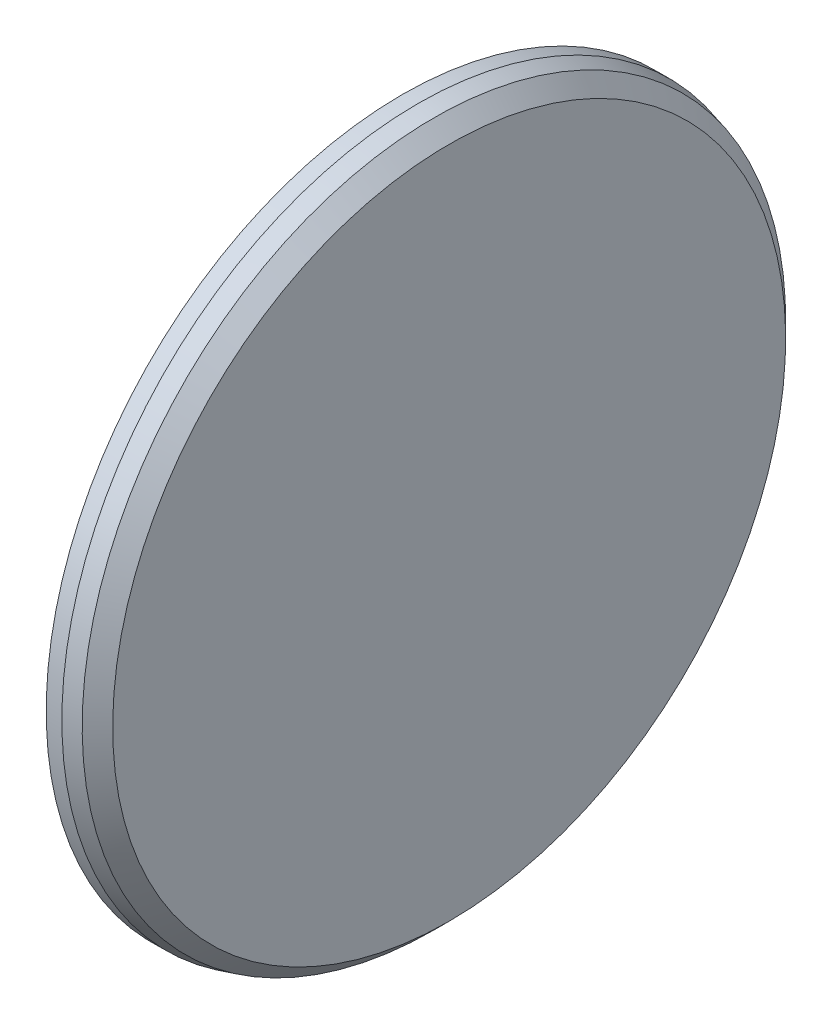
SolidWorks part; units mm, degrees
material "1060 Alloy"
ref_plane "Front Plane" through (0, 0, 0) normal (0, 0, 1) x (1, 0, 0)
ref_plane "Top Plane" through (0, 0, 0) normal (0, 1, 0) x (1, 0, 0)
ref_plane "Right Plane" through (0, 0, 0) normal (1, 0, 0) x (0, 0, -1)
sketch "Sketch1" plane through (0, 0, 0) normal (0, 0, 1) x (1, 0, 0)
  line L0 (-40, 0) -> (40, 0) construction
  line L1 (0, 0) -> (0, 74.4889) construction
  line L2 (0, 0) -> (0, -33.0272) construction
  line L3 (-40, 0) -> (40, 0)
  line L9 (-20, 455) -> (-20, 100)
  line L10 (-40, 0) -> (-40, 100)
  line L11 (-40, 100) -> (-20, 100)
  line L12 (-20, 100) -> (10, 100)
  line L13 (10, 100) -> (10, 410)
  line L14 (10, 410) -> (-20, 410)
  line L15 (-20, 410) -> (-20, 100)
  line L16 (-20, 455) -> (0, 455)
  line L17 (0, 455) -> (20.4904, 449.5096)
  line L18 (20.4904, 449.5096) -> (40, 430)
  line L19 (40, 0) -> (40, 430)
  point P3 (0, 0)
  dimension "D1" = 80
  dimension "D5" = 430
  dimension "D6" = 60
  dimension "D7" = 15
  dimension "D8" = 20
  dimension "D9" = 45
  dimension "D10" = 455
  dimension "D4" = 100
  dimension "D2" = 45
  dimension "D3" = 30
revolve "Revolve1" add sketch "Sketch1" angle 360 about L0
equation "\"A\"= 60"
equation "\"B\"= 910"
equation "\"D1@Sketch1\"=\"A\"+20"
equation "\"D5@Sketch1\"=(\"B\"-50)/2"
equation "\"D6@Sketch1\"=\"A\""
equation "\"D10@Sketch1\"=\"B\"/2"
